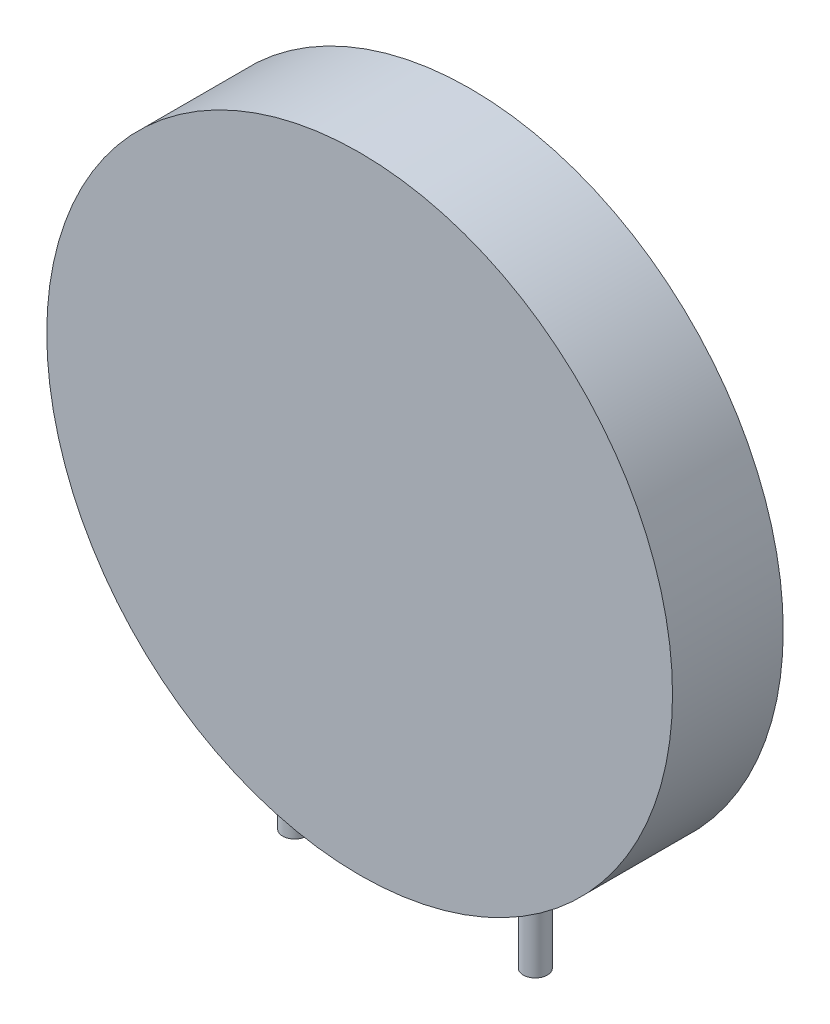
SolidWorks part; units mm, degrees
ref_plane "Front" through (0, 0, 0) normal (0, 0, 1) x (1, 0, 0)
ref_plane "Top" through (0, 0, 0) normal (0, 1, 0) x (1, 0, 0)
ref_plane "Right" through (0, 0, 0) normal (1, 0, 0) x (0, 0, -1)
sketch "Sketch1" plane through (0, 0, 0) normal (0, 0, 1) x (1, 0, 0)
  circle A0 centre (0, 0) radius 13
  dimension "D1" = 26
extrude "Boss-Extrude1" add sketch "Sketch1" along normal mid plane 4.6
sketch "Sketch2" plane through (0, 0, 0) normal (0, 1, 0) x (1, 0, 0)
  line L0 (-5, 0) -> (5, 0) construction
  circle A0 centre (-5, 0) radius 0.5
  circle A1 centre (5, 0) radius 0.5
  dimension "D2" = 1
  dimension "D1" = 10
extrude "Boss-Extrude2" add sketch "Sketch2" against normal blind 15
